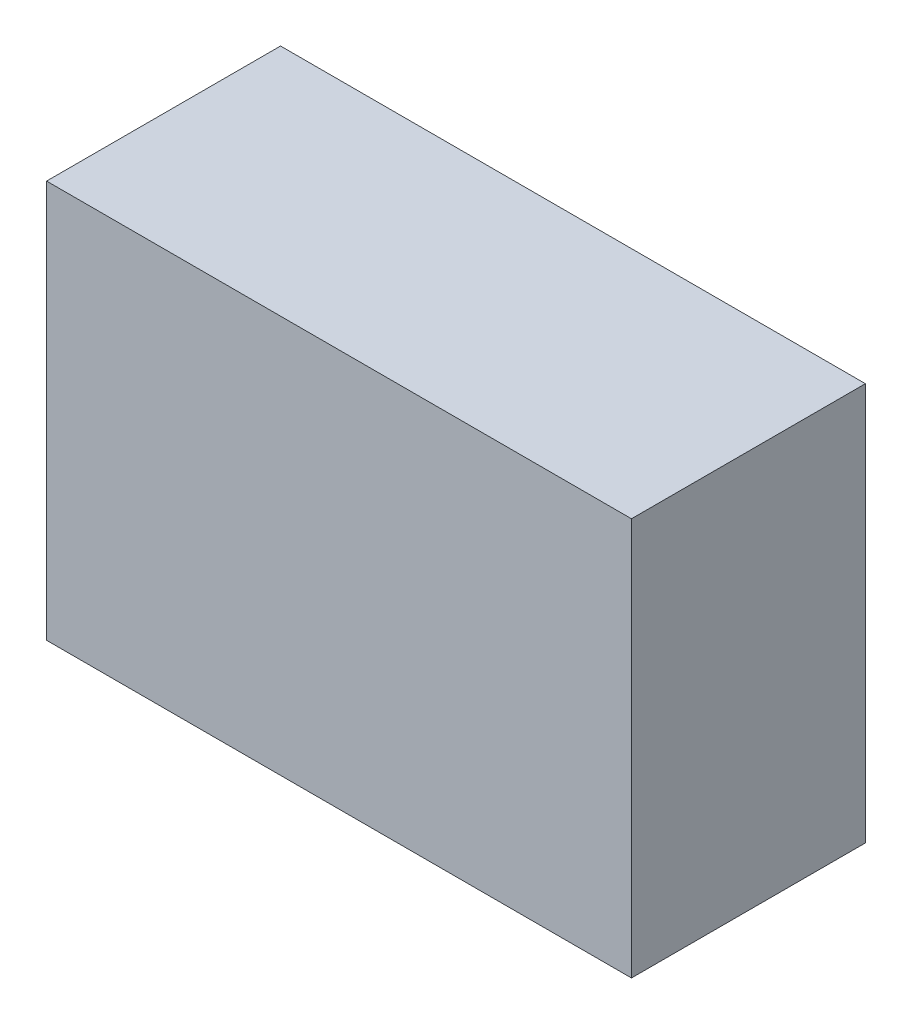
SolidWorks part; units mm, degrees
ref_plane "前视基准面" through (0, 0, 0) normal (0, 0, 1) x (1, 0, 0)
ref_plane "上视基准面" through (0, 0, 0) normal (0, 1, 0) x (1, 0, 0)
ref_plane "右视基准面" through (0, 0, 0) normal (1, 0, 0) x (0, 0, -1)
sketch "草图1" plane through (0, 0, 0) normal (0, 0, 1) x (1, 0, 0)
  line L1 (-40.4297, 27.5391) -> (9.5703, 27.5391)
  line L2 (-40.4297, 27.5391) -> (-40.4297, -6.4609)
  line L3 (-40.4297, -6.4609) -> (9.5703, -6.4609)
  line L4 (9.5703, 27.5391) -> (9.5703, -6.4609)
  dimension "D1" = 50
  dimension "D2" = 34
extrude "凸台-拉伸1" add sketch "草图1" against normal blind 20
